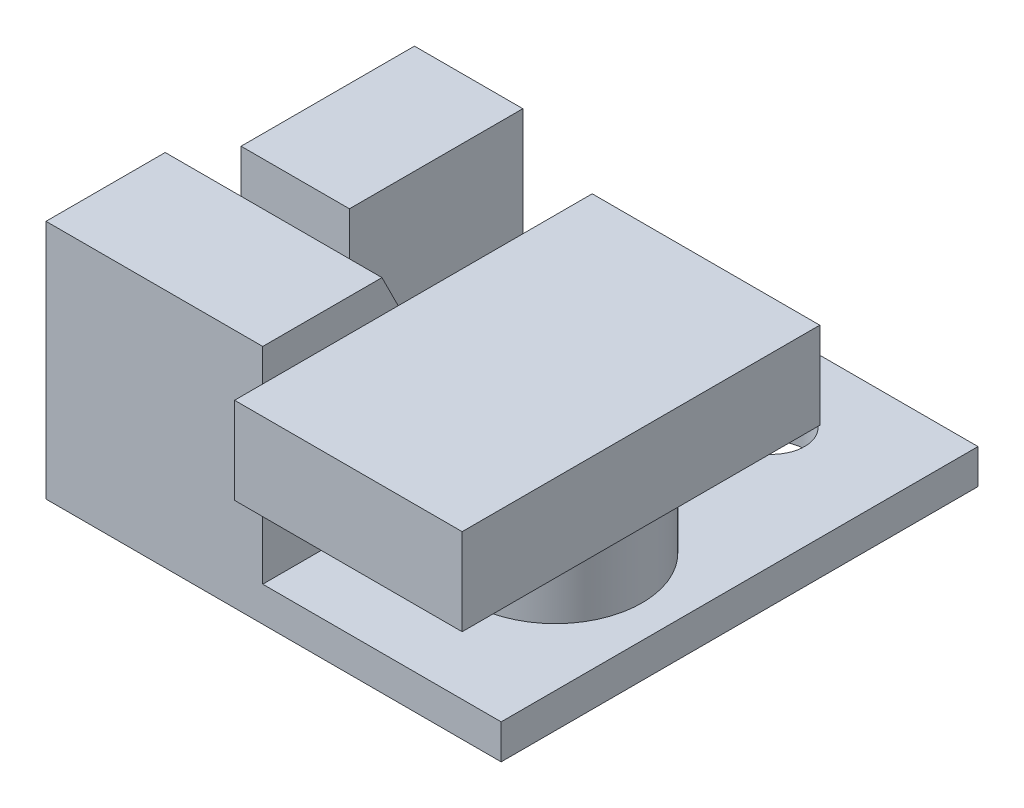
SolidWorks part; units mm, degrees
ref_plane "Front Plane" through (0, 0, 0) normal (0, 0, 1) x (1, 0, 0)
ref_plane "Top Plane" through (0, 0, 0) normal (0, 1, 0) x (1, 0, 0)
ref_plane "Right Plane" through (0, 0, 0) normal (1, 0, 0) x (0, 0, -1)
sketch "Sketch1" plane through (0, 0, 0) normal (0, 1, 0) x (1, 0, 0)
  line L1 (-10.5, 11) -> (10.5, 11)
  line L2 (-10.5, 11) -> (-10.5, -11)
  line L3 (-10.5, -11) -> (10.5, -11)
  line L4 (10.5, 11) -> (10.5, -11)
  line L5 (-10.5, 11) -> (10.5, -11) construction
  line L6 (-10.5, -11) -> (10.5, 11) construction
  point P0 (0, 0)
  dimension "D1" = 22
  dimension "D2" = 21
extrude "Boss-Extrude1" add sketch "Sketch1" along normal blind 1.6
sketch "Sketch2" plane through (0, 1.6, 0) normal (0, 1, 0) x (1, 0, 0)
  line L0 (-12.078, 8.5) -> (-1, 8.5)
  line L1 (-1, 8.5) -> (1.5, 11)
  line L2 (1.5, 11) -> (-12.078, 11)
  line L3 (-12.078, 11) -> (-12.078, 8.5)
  line L4 (-10.5, -11) -> (10.5, -11) construction
  line L5 (10.5, -11) -> (10.5, 11) construction
  line L6 (10.5, 11) -> (-10.5, 11) construction
  circle A0 centre (5, 7) radius 1.5
  dimension "D6" = 3
  dimension "D1" = 19.5
  dimension "D2" = 9
  dimension "D3" = 135
  dimension "D4" = 5.5
  dimension "D5" = 4
extrude "Cut-Extrude1" cut sketch "Sketch2" against normal blind 1.6
sketch "Sketch3" plane through (0, 1.6, 0) normal (0, 1, 0) x (1, 0, 0)
  line L0 (-10.5, 8.5) -> (-10.5, -11) construction
  line L1 (-5, 5.5) -> (-10, 5.5)
  line L2 (-5, 5.5) -> (-5, -2.5)
  line L3 (-5, -2.5) -> (-10, -2.5)
  line L4 (-10, 5.5) -> (-10, -2.5)
  line L5 (-5, 5.5) -> (-10, -2.5) construction
  line L6 (-5, -2.5) -> (-10, 5.5) construction
  line L7 (-10.5, 8.5) -> (-1, 8.5) construction
  point P0 (-7.5, 1.5)
  point P5 (-10.5, -1.25)
  dimension "D1" = 5
  dimension "D2" = 8
  dimension "D3" = 0.5
  dimension "D4" = 3
extrude "Boss-Extrude2" add sketch "Sketch3" along normal blind 8.5
sketch "Sketch4" plane through (0, 1.6, 0) normal (0, 1, 0) x (1, 0, 0)
  line L0 (-10.5, -11) -> (10.5, -11) construction
  line L1 (-0.5, -3.5) -> (-10.5, -3.5)
  line L2 (-0.5, -3.5) -> (-0.5, -11)
  line L3 (-0.5, -11) -> (-10.5, -11)
  line L4 (-10.5, -3.5) -> (-10.5, -11)
  line L5 (-0.5, -3.5) -> (-10.5, -11) construction
  line L6 (-0.5, -11) -> (-10.5, -3.5) construction
  line L7 (-10.5, 8.5) -> (-10.5, -11) construction
  point P0 (-5.5, -7.25)
  dimension "D1" = 10
  dimension "D2" = 7.5
extrude "Boss-Extrude3" add sketch "Sketch4" along normal blind 9.5
chamfer "Chamfer1" distance 4 distance2 2 1 edges at (-5.5, 11.1, 3.5)
sketch "Sketch5" plane through (0, 1.6, 0) normal (0, 1, 0) x (1, 0, 0)
  line L0 (10.5, -11) -> (10.5, 11) construction
  line L2 (-0.5, -11) -> (10.5, -11) construction
  circle A0 centre (5, -3) radius 4
  point P6 (4.0399, -11)
  dimension "D1" = 8
  dimension "D2" = 5.5
  dimension "D3" = 8
extrude "Boss-Extrude4" add sketch "Sketch5" along normal blind 4.5
sketch "Sketch6" plane through (0, 6.1, 0) normal (0, 1, 0) x (1, 0, 0)
  line L0 (10.5, -11) -> (10.5, 11) construction
  line L1 (0, 3.7) -> (10.5, 3.7)
  line L2 (0, 3.7) -> (0, -12.8)
  line L3 (0, -12.8) -> (10.5, -12.8)
  line L4 (10.5, 3.7) -> (10.5, -12.8)
  line L5 (0, 3.7) -> (10.5, -12.8) construction
  line L6 (0, -12.8) -> (10.5, 3.7) construction
  line L7 (-0.5, -11) -> (10.5, -11) construction
  point P0 (5.25, -4.55)
  dimension "D1" = 16.5
  dimension "D2" = 10.5
  dimension "D3" = 1.8
extrude "Boss-Extrude5" add sketch "Sketch6" along normal blind 4
